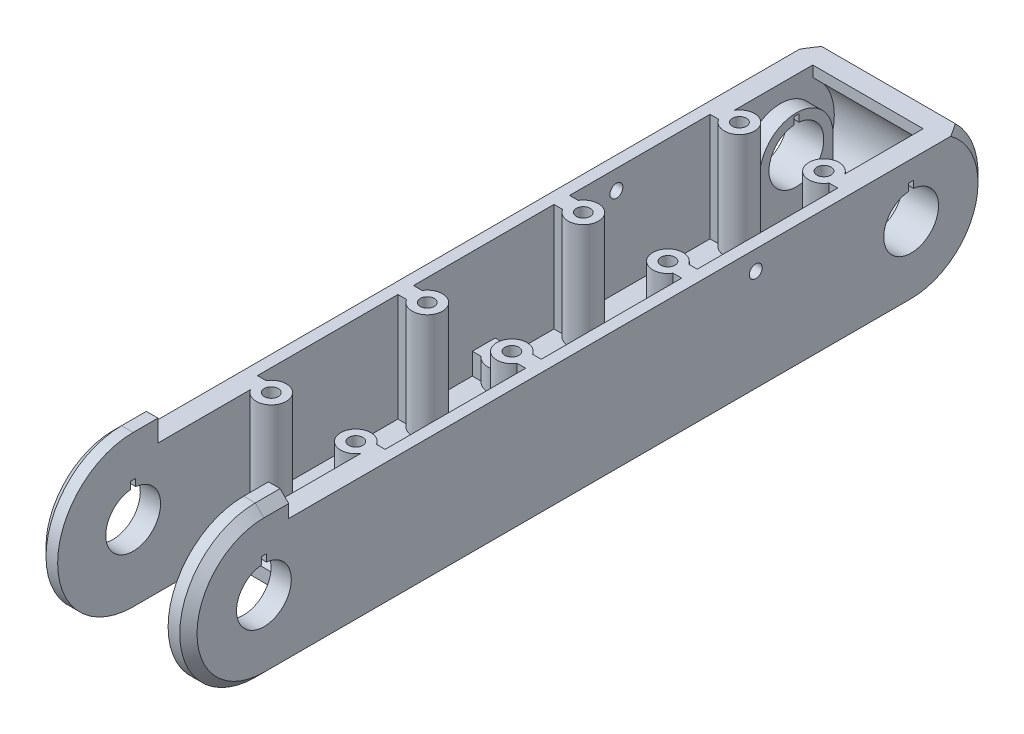
SolidWorks part; units mm, degrees
ref_plane "Front Plane" through (0, 0, 0) normal (0, 0, 1) x (1, 0, 0)
ref_plane "Top Plane" through (0, 0, 0) normal (0, 1, 0) x (1, 0, 0)
ref_plane "Right Plane" through (0, 0, 0) normal (1, 0, 0) x (0, 0, -1)
sketch "Sketch1" plane through (0, 0, 0) normal (1, 0, 0) x (0, 0, -1)
  line L0 (-75, 0) -> (75, 0) construction
  line L2 (-75, -17.5) -> (75, -17.5)
  line L4 (87.2474, 12.5) -> (-69.2474, 12.5)
  line L5 (-75, 17.5) -> (-69.2474, 17.5)
  line L6 (-69.2474, 17.5) -> (-69.2474, 12.5)
  line L7 (-69.2474, 12.5) -> (-87.2474, 12.5) construction
  arc A1 (75, -17.5) -> (87.2474, 12.5) centre (75, 0) ccw
  circle A2 centre (-75, 0) radius 6.35
  circle A3 centre (75, 0) radius 6.35
  arc A4 (-75, 17.5) -> (-75, -17.5) centre (-75, 0) ccw
  point P10 (0, 0)
  dimension "D1" = 17.5
  dimension "D3" = 17.5
  dimension "D5" = 12.7
  dimension "D2" = 150
  dimension "D4" = 5
  dimension "D6" = 18
extrude "Boss-Extrude1" add sketch "Sketch1" along normal mid plane 35
sketch "Sketch3" plane through (0, 0, 0) normal (1, 0, 0) x (0, 0, -1)
  line L0 (-75, 0) -> (75, 0) construction
  line L2 (-55, -12.5) -> (75, -12.5)
  line L3 (-75, -17.5) -> (75, -17.5) construction
  line L9 (-55, -12.5) -> (-55, -17.5)
  line L10 (-55, -17.5) -> (-92.5, -17.5)
  line L11 (-92.5, -17.5) -> (-92.5, 17.5)
  line L13 (82.5, 17.5) -> (82.5, 10)
  line L15 (82.5, 17.5) -> (-92.5, 17.5)
  line L16 (-69.2474, 17.5) -> (-75, 17.5) construction
  circle A2 centre (75, 0) radius 6.35 construction
  arc A3 (-75, 17.5) -> (-75, -17.5) centre (-75, 0) ccw construction
  arc A4 (75, -12.5) -> (82.5, 10) centre (75, 0) ccw
  point P2 (0, 0)
  point P16 (0, 0)
  point P21 (82.5, 9.9829)
  dimension "D3" = 20
  dimension "D1" = 175
  dimension "D2" = 5
extrude "Cut-Extrude1" cut sketch "Sketch3" against normal mid plane 25.6
chamfer "Chamfer1" distance 2 angle 45 9 edges at (0, -12.5, 55) (-17.5, 0, 92.5) (-17.5, -6.6144, -91.2019) (-17.5, -17.5, 0) (17.5, 0, 92.5) (17.5, -6.6144, -91.2019) (17.5, -17.5, 0) (-17.5, 17.5, 72.1237) (17.5, 17.5, 72.1237)
sketch "Sketch4" plane through (0, -12.5, 0) normal (0, 1, 0) x (1, 0, 0)
  line L0 (-9.8, -46) -> (-9.8, -9.8333) construction
  line L1 (-12.8, -53) -> (-12.8, 75) construction
  line L4 (-12.8, -53) -> (12.8, -53) construction
  line L7 (15.5, 92.5) -> (-15.5, 92.5) construction
  line L8 (-9.8, -9.8333) -> (-9.8, 26.3333) construction
  line L9 (-9.8, 26.3333) -> (-9.8, 62.5) construction
  circle A0 centre (-9.8, 62.5) radius 3.5
  circle A1 centre (-9.8, 26.3333) radius 3.5
  circle A2 centre (-9.8, -9.8333) radius 3.5
  circle A3 centre (-9.8, -46) radius 3.5
  dimension "D1" = 7
  dimension "D2" = 7
  dimension "D3" = 3
  dimension "D4" = 30
extrude "Boss-Extrude2" add sketch "Sketch4" along normal up to surface (25 mm away) up to face at (0.2, 12.5, -23.0835)
sketch "Sketch8" plane through (0, 12.5, 0) normal (0, 1, 0) x (1, 0, 0)
  circle A0 centre (-9.8, 62.5) radius 1.625
  circle A1 centre (-9.8, 26.3333) radius 1.625
  circle A2 centre (-9.8, -9.8333) radius 1.625
  circle A3 centre (-9.8, -46) radius 1.625
  dimension "D1" = 3.25
extrude "Cut-Extrude4" cut sketch "Sketch8" against normal up to surface (30 mm away) up to face at (0, -17.5, 32.5)
sketch "Sketch7" plane through (0, -17.5, 0) normal (0, -1, 0) x (1, 0, 0)
  circle A0 centre (-9.8, 46) radius 2.5
  circle A1 centre (-9.8, 9.8333) radius 2.5
  circle A2 centre (-9.8, -26.3333) radius 2.5
  circle A3 centre (-9.8, -62.5) radius 2.5
  circle A4 centre (-9.8, 46) radius 1.625 construction
  circle A5 centre (-9.8, 9.8333) radius 1.625 construction
  circle A6 centre (-9.8, -26.3333) radius 1.625 construction
  circle A8 centre (-9.8, -62.5) radius 1.625 construction
  dimension "D1" = 5
extrude "Cut-Extrude3" cut sketch "Sketch7" against normal blind 3.5
sketch "Sketch9" plane through (0, -12.5, 0) normal (0, 1, 0) x (1, 0, 0)
  line L0 (-9.8, 26.3333) -> (-9.8, -9.8333) construction
  circle A0 centre (-9.8, 8.25) radius 4
  circle A1 centre (-9.8, 8.25) radius 1.625
  point P6 (-9.8, 8.25)
  dimension "D1" = 8
  dimension "D2" = 3.25
extrude "Boss-Extrude3" add sketch "Sketch9" along normal blind 5 and the other way up to surface (5 mm away) other way up to face at (-9.8, -17.5, 43.5)
sketch "Sketch11" plane through (0, -17.5, 0) normal (0, -1, 0) x (1, 0, 0)
  line L0 (-9.8, 9.8333) -> (-9.8, -26.3333) construction
  circle A0 centre (-9.8, -8.25) radius 2.75
  point P6 (-9.8, -8.25)
  dimension "D1" = 5.5
extrude "Cut-Extrude5" cut sketch "Sketch11" against normal blind 3
mirror "Mirror1" about plane through (0, 0, 0) normal (1, 0, 0) of "Cut-Extrude5", "Boss-Extrude3", "Cut-Extrude3", "Boss-Extrude2", "Cut-Extrude4"
sketch "Sketch12" plane through (0, -17.5, 0) normal (0, -1, 0) x (1, 0, 0)
  circle A0 centre (9.8, -8.25) radius 1.625
  dimension "D1" = 3.25
extrude "Cut-Extrude6" cut sketch "Sketch12" against normal through all both and the other way through all
sketch "Sketch13" plane through (-12.8, 0, 0) normal (1, 0, 0) x (0, 0, -1)
  line L0 (66.5, 0) -> (66.5, -12.5)
  line L2 (66.5, -12.5) -> (83.5, -12.5)
  line L3 (83.5, -12.5) -> (83.5, 0)
  line L4 (64.3028, -12.5) -> (75, -12.5) construction
  arc A0 (83.5, 0) -> (66.5, 0) centre (75, 0) ccw
  dimension "D1" = 17
extrude "Boss-Extrude4" add sketch "Sketch13" along normal blind 3.7
sketch "Sketch14" plane through (-12.8, 0, 0) normal (-1, 0, 0) x (0, 0, 1)
  circle A0 centre (-75, 0) radius 6.35
  dimension "D1" = 12.7
extrude "Cut-Extrude7" cut sketch "Sketch14" against normal up to surface (3.7 mm away) up to face at (-9.1, -5.2938, -75.0631)
sketch "Sketch15" plane through (0, 12.5, 0) normal (0, 1, 0) x (1, 0, 0)
  line L1 (-12.8, 60.6972) -> (-14.8, 60.6972)
  line L2 (-12.8, 60.6972) -> (-12.8, 28.1361)
  line L3 (-12.8, 28.1361) -> (-14.8, 28.1361)
  line L4 (-14.8, 60.6972) -> (-14.8, 28.1361)
  line L5 (-12.8, 24.5306) -> (-14.8, 24.5306)
  line L6 (-12.8, 24.5306) -> (-12.8, 10.8958)
  line L7 (-12.8, 10.8958) -> (-14.8, 10.8958)
  line L8 (-14.8, 24.5306) -> (-14.8, 10.8958)
  line L9 (-12.8, 5.6042) -> (-14.8, 5.6042)
  line L10 (-12.8, 5.6042) -> (-12.8, -8.0306)
  line L11 (-12.8, -8.0306) -> (-14.8, -8.0306)
  line L12 (-14.8, 5.6042) -> (-14.8, -8.0306)
  line L13 (-12.8, -11.6361) -> (-14.8, -11.6361)
  line L14 (-12.8, -11.6361) -> (-12.8, -44.1972)
  line L15 (-12.8, -44.1972) -> (-14.8, -44.1972)
  line L16 (-14.8, -11.6361) -> (-14.8, -44.1972)
  dimension "D1" = 2
extrude "Cut-Extrude8" cut sketch "Sketch15" against normal up to surface (25 mm away) up to face at (-0.7, -12.5, -13.1538)
sketch "Sketch16" plane through (0, 12.5, 0) normal (0, 1, 0) x (1, 0, 0)
  line L1 (-12.8, 5.6042) -> (-14.8, 5.6042)
  line L2 (-12.8, 5.6042) -> (-12.8, 10.8958)
  line L3 (-12.8, 10.8958) -> (-14.8, 10.8958)
  line L4 (-14.8, 5.6042) -> (-14.8, 10.8958)
extrude "Cut-Extrude9" cut sketch "Sketch16" against normal up to surface (20 mm away) up to face at (-9.3, -7.5, -8.25)
mirror "Mirror2" about plane through (0, 0, 0) normal (1, 0, 0) of "Cut-Extrude9", "Boss-Extrude4", "Cut-Extrude7", "Cut-Extrude6", "Cut-Extrude8"
sketch "Sketch17" plane through (17.5, 0, 0) normal (1, 0, 0) x (0, 0, -1)
  line L0 (39, 12.5) -> (39, -15.5) construction
  line L1 (84.1652, 12.5) -> (-69.2474, 12.5) construction
  line L2 (-75, -15.5) -> (75, -15.5) construction
  line L3 (88.2759, 8) -> (-10.2759, 8) construction
  circle A0 centre (39, 8) radius 1.5
  arc A2 (75, -15.5) -> (84.1652, 12.5) centre (75, 0) ccw construction
  circle A3 centre (75, 0) radius 6.35 construction
  point P16 (0, 0)
  point P18 (39, 8)
  dimension "D3" = 3
  dimension "D1" = 36
  dimension "D2" = 8
extrude "Cut-Extrude10" cut sketch "Sketch17" against normal up to surface (35 mm away) up to face at (-17.5, 3.613, 22.4469)
sketch "Sketch18" plane through (-17.5, 0, 0) normal (-1, 0, 0) x (0, 0, 1)
  line L1 (-75.6, 8) -> (-74.4, 8)
  line L2 (-75.6, 8) -> (-75.6, 0)
  line L3 (-75.6, 0) -> (-74.4, 0)
  line L4 (-74.4, 8) -> (-74.4, 0)
  circle A0 centre (-75, 0) radius 6.35 construction
  point P4 (-75, 0)
  dimension "D1" = 1.2
  dimension "D2" = 8
extrude "Cut-Extrude11" cut sketch "Sketch18" against normal up to surface (35 mm away) up to face at (17.5, 8, -40.5)
mirror "Mirror3" about plane through (0, 0, 0) normal (0, 0, 1) of "Cut-Extrude11"
